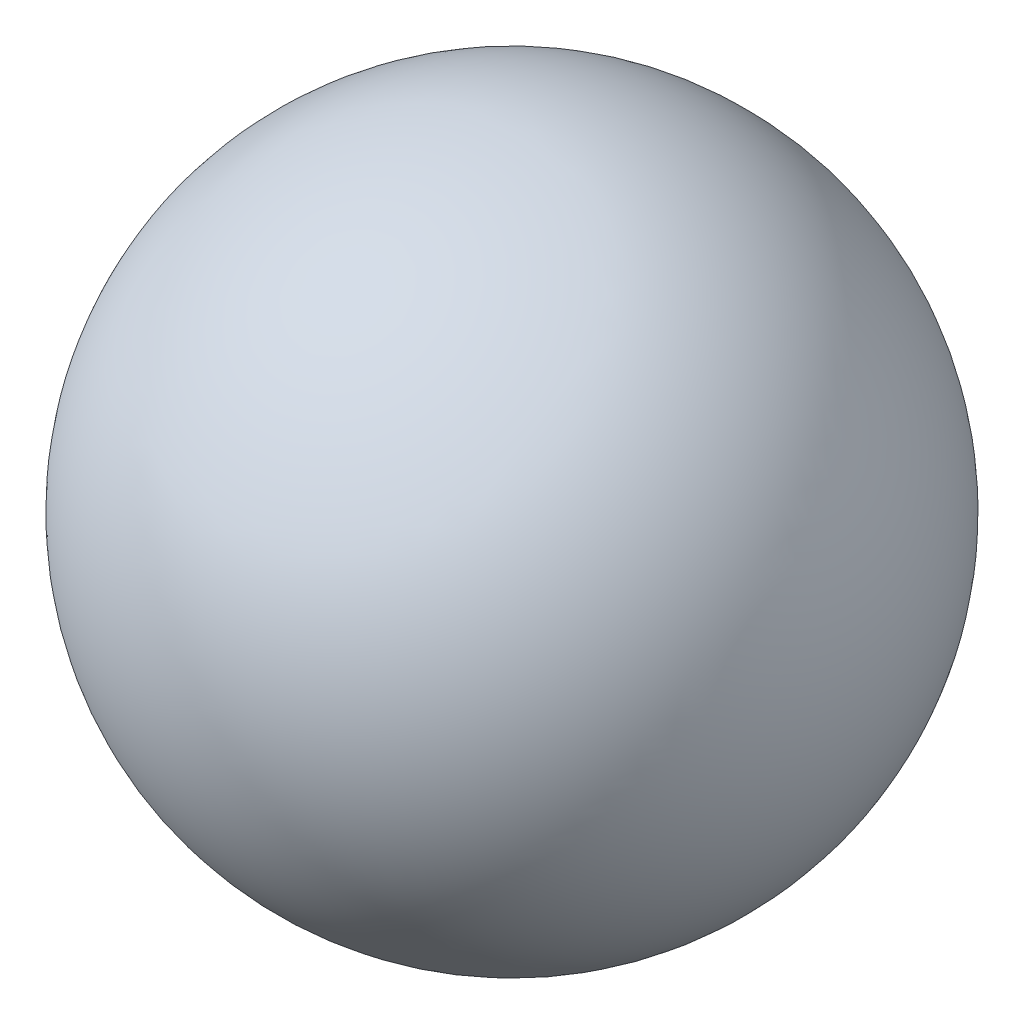
SolidWorks part; units mm, degrees
ref_plane "Front Plane" through (0, 0, 0) normal (0, 0, 1) x (1, 0, 0)
ref_plane "Top Plane" through (0, 0, 0) normal (0, 1, 0) x (1, 0, 0)
ref_plane "Right Plane" through (0, 0, 0) normal (1, 0, 0) x (0, 0, -1)
sketch "Sketch1" plane through (0, 0, 0) normal (0, 0, 1) x (1, 0, 0)
  line L0 (-60, 0) -> (60, 0) construction
  line L1 (-60, 0) -> (60, 0)
  arc A0 (60, 0) -> (-60, 0) centre (0, 0) ccw
  dimension "D1" = 60
revolve "Revolve1" add sketch "Sketch1" angle 360 about L0
ref_plane "Plane1" [suppressed] through (60, 0, 0) normal (1, 0, 0) x (0, 0, -1)
sketch "Sketch2" [suppressed] plane through (60, 0, 0) normal (1, 0, 0) x (0, 0, -1)
  circle A0 centre (0, 0) radius 30
  dimension "D1" = 60
extrude "Boss-Extrude1" [suppressed] add sketch "Sketch2" against normal blind 10
fillet "Fillet1" [suppressed] radius 50
ref_plane "Plane2" [suppressed] through (65, 0, 0) normal (1, 0, 0) x (0, 0, -1)
sketch "Sketch4" [suppressed] plane through (65, 0, 0) normal (1, 0, 0) x (0, 0, -1)
  circle A0 centre (0, 0) radius 5
  dimension "D1" = 10
extrude "Boss-Extrude2" [suppressed] add sketch "Sketch4" against normal blind 10
loft "Loft1" [suppressed] add
